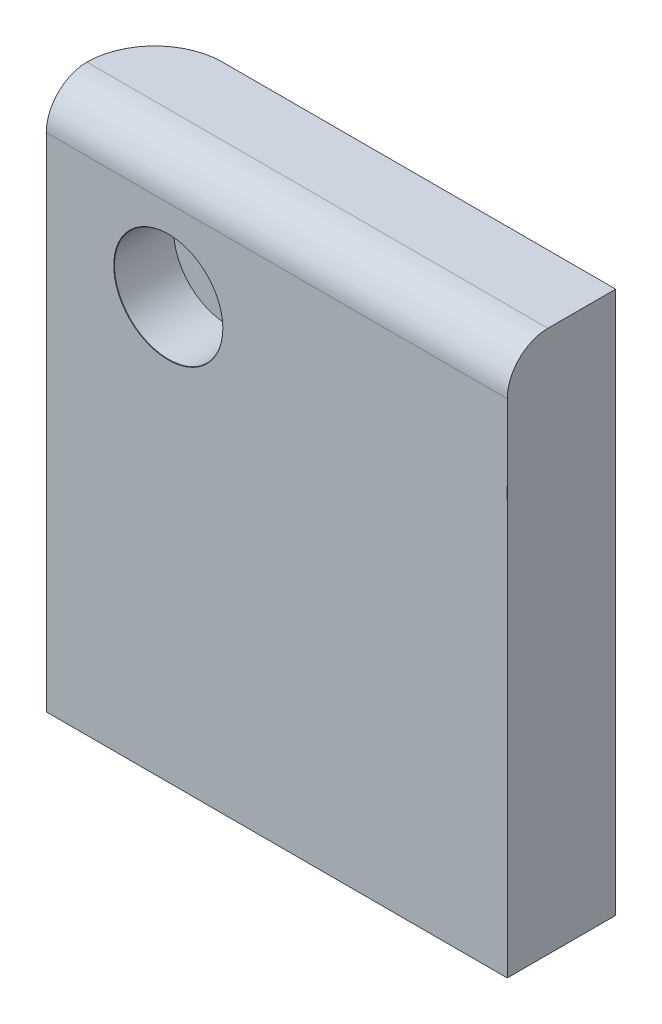
SolidWorks part; units mm, degrees
material "K110"
ref_plane "Front Plane" through (0, 0, 0) normal (0, 0, 1) x (1, 0, 0)
ref_plane "Top Plane" through (0, 0, 0) normal (0, 1, 0) x (1, 0, 0)
ref_plane "Right Plane" through (0, 0, 0) normal (1, 0, 0) x (0, 0, -1)
sketch "Sketch1" plane through (0, 0, 0) normal (0, 1, 0) x (1, 0, 0)
  line L1 (-23.5, -4) -> (23.5, -4)
  line L2 (-23.5, -4) -> (-23.5, 4)
  line L3 (-23.5, 4) -> (23.5, 4)
  line L4 (23.5, -4) -> (23.5, 4)
  line L5 (-23.5, -4) -> (23.5, 4) construction
  line L6 (-23.5, 4) -> (23.5, -4) construction
  point P0 (0, 0)
  dimension "D1" = 8
  dimension "D2" = 47
extrude "Boss-Extrude1" add sketch "Sketch1" against normal blind 40
fillet "Fillet1" radius 3 1 edges at (0, 0, 4)
fillet "Fillet2" radius 5 2 edges at (-23.5, -20, -4) (23.5, -20, -4)
hole_wizard "CBORE for M4 Hex Socket Head Cap Screw1" positions "Sketch6" profile "Sketch3" counterbore size "M4" standard "ISO" end condition through all
sketch "Sketch6" plane through (0, 0, 4) normal (0, 0, 1) x (1, 0, 0)
  line L1 (23.5, -3) -> (-23.5, -3) construction
  line L2 (-23.5, -40) -> (-23.5, -3) construction
  line L3 (23.5, -40) -> (23.5, -3) construction
  point P0 (-14.5, -9)
  point P2 (14.5, -9)
  dimension "D1" = 6
  dimension "D2" = 9
  dimension "D3" = 9
sketch "Sketch3" plane through (-14.5, -9, 4) normal (1, 0, 0) x (0, -1, 0)
  line L0 (0, 0) -> (0, 8)
  line L1 (0, 8) -> (2.15, 8)
  line L3 (2.15, 8) -> (2.15, 4.4)
  line L4 (4, 4.4) -> (2.15, 4.4)
  line L5 (4, 4.4) -> (4, 0.025)
  line L6 (4, 0.025) -> (4.025, 0)
  line L7 (4.025, 0) -> (0, 0)
  line L8 (-4, 0.025) -> (-4.025, 0) construction
  line L11 (0, -6.35) -> (0, 107.95) construction
  dimension "Thru Hole Dia." = 4.3
  dimension "Thru Hole Depth" = 8
  dimension "C'Bore Dia." = 8
  dimension "C'Bore Depth" = 4.4
  dimension "Near C'Sink Dia." = 8.05
  dimension "Near C'Sink Angle" = 90
sketch "Sketch5" plane through (0, 0, 4) normal (0, 0, 1) x (1, 0, 0)
  line L0 (23.5, -40) -> (23.5, -3) construction
  line L1 (23.5, -40) -> (10.5, -40)
  line L2 (23.5, -40) -> (23.5, 4.9978)
  line L3 (23.5, 4.9978) -> (10.5, 4.9978)
  line L4 (10.5, -40) -> (10.5, 4.9978)
  line L6 (19.4978, -7.0022) -> (29.5, -7.0022) construction
  dimension "D1" = 12
  dimension "D2" = 13
extrude "Cut-Extrude1" cut sketch "Sketch5" against normal up to next
